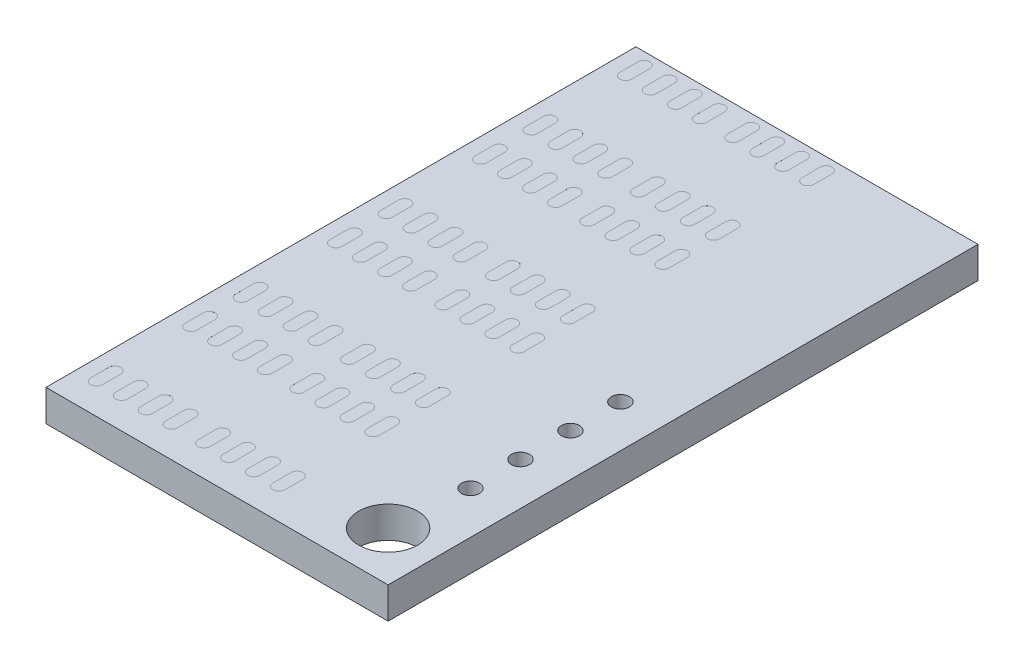
SolidWorks part; units mm, degrees
ref_plane "Front" through (0, 0, 0) normal (0, 0, 1) x (1, 0, 0)
ref_plane "Top" through (0, 0, 0) normal (0, 1, 0) x (1, 0, 0)
ref_plane "Right" through (0, 0, 0) normal (1, 0, 0) x (0, 0, -1)
sketch "Эскиз1" plane through (0, 0, 0) normal (0, 1, 0) x (1, 0, 0)
  line L1 (-8.7, -15) -> (8.7, -15)
  line L2 (-8.7, -15) -> (-8.7, 15)
  line L3 (-8.7, 15) -> (8.7, 15)
  line L4 (8.7, -15) -> (8.7, 15)
  line L5 (-8.7, -15) -> (8.7, 15) construction
  line L6 (-8.7, 15) -> (8.7, -15) construction
  point P0 (0, 0)
  dimension "D1" = 17.4
  dimension "D2" = 30
extrude "Бобышка-Вытянуть1" add sketch "Эскиз1" along normal blind 1.6
sketch "Эскиз2" plane through (0, 1.6, 0) normal (0, 1, 0) x (1, 0, 0)
  line L0 (-8.7, -15) -> (8.7, -15) construction
  line L1 (8.7, -15) -> (8.7, 15) construction
  line L2 (6.541, -8.65) -> (6.541, -1.03) construction
  circle A0 centre (6.2, -12.5) radius 1.5
  circle A1 centre (6.541, -1.03) radius 0.457
  circle A2 centre (6.541, -3.57) radius 0.457
  circle A3 centre (6.541, -6.11) radius 0.457
  circle A4 centre (6.541, -8.65) radius 0.457
  dimension "D1" = 3
  dimension "D4" = 0.914
  dimension "D5" = 0.914
  dimension "D6" = 0.914
  dimension "D7" = 0.914
  dimension "D11" = 2.159
  dimension "D2" = 2.5
  dimension "D3" = 2.5
  dimension "D8" = 2.54
  dimension "D9" = 2.54
  dimension "D10" = 2.54
  dimension "D12" = 13.97
extrude "Вырез-Вытянуть1" cut sketch "Эскиз2" against normal blind 1.6
sketch "Эскиз3" plane through (0, 1.6, 0) normal (0, 1, 0) x (1, 0, 0)
  line L0 (-7.684, 14.39) -> (-7.684, 13.47) construction
  line L1 (-7.384, 14.39) -> (-7.384, 13.47)
  line L2 (-7.984, 14.39) -> (-7.984, 13.47)
  line L3 (8.7, 15) -> (-8.7, 15) construction
  line L4 (-8.7, 15) -> (-8.7, -15) construction
  line L5 (-6.414, 14.39) -> (-6.414, 13.47) construction
  line L6 (-6.114, 14.39) -> (-6.114, 13.47)
  line L7 (-6.714, 14.39) -> (-6.714, 13.47)
  line L8 (-5.144, 14.39) -> (-5.144, 13.47) construction
  line L9 (-4.844, 14.39) -> (-4.844, 13.47)
  line L10 (-5.444, 14.39) -> (-5.444, 13.47)
  line L11 (-3.874, 14.39) -> (-3.874, 13.47) construction
  line L12 (-3.574, 14.39) -> (-3.574, 13.47)
  line L13 (-4.174, 14.39) -> (-4.174, 13.47)
  line L14 (-6.414, 9.59) -> (-6.414, 8.67) construction
  line L15 (-6.114, 9.59) -> (-6.114, 8.67)
  line L16 (-6.714, 9.59) -> (-6.714, 8.67)
  line L17 (-5.144, 9.59) -> (-5.144, 8.67) construction
  line L18 (-4.844, 9.59) -> (-4.844, 8.67)
  line L19 (-5.444, 9.59) -> (-5.444, 8.67)
  line L20 (-3.874, 9.59) -> (-3.874, 8.67) construction
  line L21 (-3.574, 9.59) -> (-3.574, 8.67)
  line L22 (-4.174, 9.59) -> (-4.174, 8.67)
  line L23 (-7.684, 9.59) -> (-7.684, 8.67) construction
  line L24 (-7.384, 9.59) -> (-7.384, 8.67)
  line L25 (-7.984, 9.59) -> (-7.984, 8.67)
  line L26 (-2.224, 14.39) -> (-2.224, 13.47) construction
  line L27 (-1.924, 14.39) -> (-1.924, 13.47)
  line L28 (-2.524, 14.39) -> (-2.524, 13.47)
  line L29 (-0.954, 14.39) -> (-0.954, 13.47) construction
  line L30 (-0.654, 14.39) -> (-0.654, 13.47)
  line L31 (-1.254, 14.39) -> (-1.254, 13.47)
  line L32 (0.316, 14.39) -> (0.316, 13.47) construction
  line L33 (0.616, 14.39) -> (0.616, 13.47)
  line L34 (0.016, 14.39) -> (0.016, 13.47)
  line L35 (1.586, 14.39) -> (1.586, 13.47) construction
  line L36 (1.886, 14.39) -> (1.886, 13.47)
  line L37 (1.286, 14.39) -> (1.286, 13.47)
  line L38 (-0.954, 9.59) -> (-0.954, 8.67) construction
  line L39 (-0.654, 9.59) -> (-0.654, 8.67)
  line L40 (-1.254, 9.59) -> (-1.254, 8.67)
  line L41 (0.316, 9.59) -> (0.316, 8.67) construction
  line L42 (0.616, 9.59) -> (0.616, 8.67)
  line L43 (0.016, 9.59) -> (0.016, 8.67)
  line L44 (1.586, 9.59) -> (1.586, 8.67) construction
  line L45 (1.886, 9.59) -> (1.886, 8.67)
  line L46 (1.286, 9.59) -> (1.286, 8.67)
  line L47 (-2.224, 9.59) -> (-2.224, 8.67) construction
  line L48 (-1.924, 9.59) -> (-1.924, 8.67)
  line L49 (-2.524, 9.59) -> (-2.524, 8.67)
  line L50 (-2.224, 7.02) -> (-2.224, 6.1) construction
  line L51 (-1.924, 7.02) -> (-1.924, 6.1)
  line L52 (-2.524, 7.02) -> (-2.524, 6.1)
  line L53 (-0.954, 7.02) -> (-0.954, 6.1) construction
  line L54 (-0.654, 7.02) -> (-0.654, 6.1)
  line L55 (-1.254, 7.02) -> (-1.254, 6.1)
  line L56 (0.316, 7.02) -> (0.316, 6.1) construction
  line L57 (0.616, 7.02) -> (0.616, 6.1)
  line L58 (0.016, 7.02) -> (0.016, 6.1)
  line L59 (1.586, 7.02) -> (1.586, 6.1) construction
  line L60 (1.886, 7.02) -> (1.886, 6.1)
  line L61 (1.286, 7.02) -> (1.286, 6.1)
  line L62 (-0.954, 2.22) -> (-0.954, 1.3) construction
  line L63 (-0.654, 2.22) -> (-0.654, 1.3)
  line L64 (-1.254, 2.22) -> (-1.254, 1.3)
  line L65 (0.316, 2.22) -> (0.316, 1.3) construction
  line L66 (0.616, 2.22) -> (0.616, 1.3)
  line L67 (0.016, 2.22) -> (0.016, 1.3)
  line L68 (1.586, 2.22) -> (1.586, 1.3) construction
  line L69 (1.886, 2.22) -> (1.886, 1.3)
  line L70 (1.286, 2.22) -> (1.286, 1.3)
  line L71 (-2.224, 2.22) -> (-2.224, 1.3) construction
  line L72 (-1.924, 2.22) -> (-1.924, 1.3)
  line L73 (-2.524, 2.22) -> (-2.524, 1.3)
  line L74 (-2.224, -0.35) -> (-2.224, -1.27) construction
  line L75 (-1.924, -0.35) -> (-1.924, -1.27)
  line L76 (-2.524, -0.35) -> (-2.524, -1.27)
  line L77 (-0.954, -0.35) -> (-0.954, -1.27) construction
  line L78 (-0.654, -0.35) -> (-0.654, -1.27)
  line L79 (-1.254, -0.35) -> (-1.254, -1.27)
  line L80 (0.316, -0.35) -> (0.316, -1.27) construction
  line L81 (0.616, -0.35) -> (0.616, -1.27)
  line L82 (0.016, -0.35) -> (0.016, -1.27)
  line L83 (1.586, -0.35) -> (1.586, -1.27) construction
  line L84 (1.886, -0.35) -> (1.886, -1.27)
  line L85 (1.286, -0.35) -> (1.286, -1.27)
  line L86 (-0.954, -5.15) -> (-0.954, -6.07) construction
  line L87 (-0.654, -5.15) -> (-0.654, -6.07)
  line L88 (-1.254, -5.15) -> (-1.254, -6.07)
  line L89 (0.316, -5.15) -> (0.316, -6.07) construction
  line L90 (0.616, -5.15) -> (0.616, -6.07)
  line L91 (0.016, -5.15) -> (0.016, -6.07)
  line L92 (1.586, -5.15) -> (1.586, -6.07) construction
  line L93 (1.886, -5.15) -> (1.886, -6.07)
  line L94 (1.286, -5.15) -> (1.286, -6.07)
  line L95 (-2.224, -5.15) -> (-2.224, -6.07) construction
  line L96 (-1.924, -5.15) -> (-1.924, -6.07)
  line L97 (-2.524, -5.15) -> (-2.524, -6.07)
  line L98 (-2.224, -7.72) -> (-2.224, -8.64) construction
  line L99 (-1.924, -7.72) -> (-1.924, -8.64)
  line L100 (-2.524, -7.72) -> (-2.524, -8.64)
  line L101 (-0.954, -7.72) -> (-0.954, -8.64) construction
  line L102 (-0.654, -7.72) -> (-0.654, -8.64)
  line L103 (-1.254, -7.72) -> (-1.254, -8.64)
  line L104 (0.316, -7.72) -> (0.316, -8.64) construction
  line L105 (0.616, -7.72) -> (0.616, -8.64)
  line L106 (0.016, -7.72) -> (0.016, -8.64)
  line L107 (1.586, -7.72) -> (1.586, -8.64) construction
  line L108 (1.886, -7.72) -> (1.886, -8.64)
  line L109 (1.286, -7.72) -> (1.286, -8.64)
  line L110 (-0.954, -12.52) -> (-0.954, -13.44) construction
  line L111 (-0.654, -12.52) -> (-0.654, -13.44)
  line L112 (-1.254, -12.52) -> (-1.254, -13.44)
  line L113 (0.316, -12.52) -> (0.316, -13.44) construction
  line L114 (0.616, -12.52) -> (0.616, -13.44)
  line L115 (0.016, -12.52) -> (0.016, -13.44)
  line L116 (1.586, -12.52) -> (1.586, -13.44) construction
  line L117 (1.886, -12.52) -> (1.886, -13.44)
  line L118 (1.286, -12.52) -> (1.286, -13.44)
  line L119 (-2.224, -12.52) -> (-2.224, -13.44) construction
  line L120 (-1.924, -12.52) -> (-1.924, -13.44)
  line L121 (-2.524, -12.52) -> (-2.524, -13.44)
  line L122 (-7.684, 7.02) -> (-7.684, 6.1) construction
  line L123 (-7.384, 7.02) -> (-7.384, 6.1)
  line L124 (-7.984, 7.02) -> (-7.984, 6.1)
  line L125 (-6.414, 7.02) -> (-6.414, 6.1) construction
  line L126 (-6.114, 7.02) -> (-6.114, 6.1)
  line L127 (-6.714, 7.02) -> (-6.714, 6.1)
  line L128 (-5.144, 7.02) -> (-5.144, 6.1) construction
  line L129 (-4.844, 7.02) -> (-4.844, 6.1)
  line L130 (-5.444, 7.02) -> (-5.444, 6.1)
  line L131 (-3.874, 7.02) -> (-3.874, 6.1) construction
  line L132 (-3.574, 7.02) -> (-3.574, 6.1)
  line L133 (-4.174, 7.02) -> (-4.174, 6.1)
  line L134 (-6.414, 2.22) -> (-6.414, 1.3) construction
  line L135 (-6.114, 2.22) -> (-6.114, 1.3)
  line L136 (-6.714, 2.22) -> (-6.714, 1.3)
  line L137 (-5.144, 2.22) -> (-5.144, 1.3) construction
  line L138 (-4.844, 2.22) -> (-4.844, 1.3)
  line L139 (-5.444, 2.22) -> (-5.444, 1.3)
  line L140 (-3.874, 2.22) -> (-3.874, 1.3) construction
  line L141 (-3.574, 2.22) -> (-3.574, 1.3)
  line L142 (-4.174, 2.22) -> (-4.174, 1.3)
  line L143 (-7.684, 2.22) -> (-7.684, 1.3) construction
  line L144 (-7.384, 2.22) -> (-7.384, 1.3)
  line L145 (-7.984, 2.22) -> (-7.984, 1.3)
  line L146 (-7.684, -0.35) -> (-7.684, -1.27) construction
  line L147 (-7.384, -0.35) -> (-7.384, -1.27)
  line L148 (-7.984, -0.35) -> (-7.984, -1.27)
  line L149 (-6.414, -0.35) -> (-6.414, -1.27) construction
  line L150 (-6.114, -0.35) -> (-6.114, -1.27)
  line L151 (-6.714, -0.35) -> (-6.714, -1.27)
  line L152 (-5.144, -0.35) -> (-5.144, -1.27) construction
  line L153 (-4.844, -0.35) -> (-4.844, -1.27)
  line L154 (-5.444, -0.35) -> (-5.444, -1.27)
  line L155 (-3.874, -0.35) -> (-3.874, -1.27) construction
  line L156 (-3.574, -0.35) -> (-3.574, -1.27)
  line L157 (-4.174, -0.35) -> (-4.174, -1.27)
  line L158 (-6.414, -5.15) -> (-6.414, -6.07) construction
  line L159 (-6.114, -5.15) -> (-6.114, -6.07)
  line L160 (-6.714, -5.15) -> (-6.714, -6.07)
  line L161 (-5.144, -5.15) -> (-5.144, -6.07) construction
  line L162 (-4.844, -5.15) -> (-4.844, -6.07)
  line L163 (-5.444, -5.15) -> (-5.444, -6.07)
  line L164 (-3.874, -5.15) -> (-3.874, -6.07) construction
  line L165 (-3.574, -5.15) -> (-3.574, -6.07)
  line L166 (-4.174, -5.15) -> (-4.174, -6.07)
  line L167 (-7.684, -5.15) -> (-7.684, -6.07) construction
  line L168 (-7.384, -5.15) -> (-7.384, -6.07)
  line L169 (-7.984, -5.15) -> (-7.984, -6.07)
  line L170 (-7.684, -7.72) -> (-7.684, -8.64) construction
  line L171 (-7.384, -7.72) -> (-7.384, -8.64)
  line L172 (-7.984, -7.72) -> (-7.984, -8.64)
  line L173 (-6.414, -7.72) -> (-6.414, -8.64) construction
  line L174 (-6.114, -7.72) -> (-6.114, -8.64)
  line L175 (-6.714, -7.72) -> (-6.714, -8.64)
  line L176 (-5.144, -7.72) -> (-5.144, -8.64) construction
  line L177 (-4.844, -7.72) -> (-4.844, -8.64)
  line L178 (-5.444, -7.72) -> (-5.444, -8.64)
  line L179 (-3.874, -7.72) -> (-3.874, -8.64) construction
  line L180 (-3.574, -7.72) -> (-3.574, -8.64)
  line L181 (-4.174, -7.72) -> (-4.174, -8.64)
  line L182 (-6.414, -12.52) -> (-6.414, -13.44) construction
  line L183 (-6.114, -12.52) -> (-6.114, -13.44)
  line L184 (-6.714, -12.52) -> (-6.714, -13.44)
  line L185 (-5.144, -12.52) -> (-5.144, -13.44) construction
  line L186 (-4.844, -12.52) -> (-4.844, -13.44)
  line L187 (-5.444, -12.52) -> (-5.444, -13.44)
  line L188 (-3.874, -12.52) -> (-3.874, -13.44) construction
  line L189 (-3.574, -12.52) -> (-3.574, -13.44)
  line L190 (-4.174, -12.52) -> (-4.174, -13.44)
  line L191 (-7.684, -12.52) -> (-7.684, -13.44) construction
  line L192 (-7.384, -12.52) -> (-7.384, -13.44)
  line L193 (-7.984, -12.52) -> (-7.984, -13.44)
  arc A0 (-7.384, 14.39) -> (-7.984, 14.39) centre (-7.684, 14.39) ccw
  arc A1 (-7.984, 13.47) -> (-7.384, 13.47) centre (-7.684, 13.47) ccw
  arc A2 (-6.114, 14.39) -> (-6.714, 14.39) centre (-6.414, 14.39) ccw
  arc A3 (-6.714, 13.47) -> (-6.114, 13.47) centre (-6.414, 13.47) ccw
  arc A4 (-4.844, 14.39) -> (-5.444, 14.39) centre (-5.144, 14.39) ccw
  arc A5 (-5.444, 13.47) -> (-4.844, 13.47) centre (-5.144, 13.47) ccw
  arc A6 (-3.574, 14.39) -> (-4.174, 14.39) centre (-3.874, 14.39) ccw
  arc A7 (-4.174, 13.47) -> (-3.574, 13.47) centre (-3.874, 13.47) ccw
  arc A8 (-6.114, 9.59) -> (-6.714, 9.59) centre (-6.414, 9.59) ccw
  arc A9 (-6.714, 8.67) -> (-6.114, 8.67) centre (-6.414, 8.67) ccw
  arc A10 (-4.844, 9.59) -> (-5.444, 9.59) centre (-5.144, 9.59) ccw
  arc A11 (-5.444, 8.67) -> (-4.844, 8.67) centre (-5.144, 8.67) ccw
  arc A12 (-3.574, 9.59) -> (-4.174, 9.59) centre (-3.874, 9.59) ccw
  arc A13 (-4.174, 8.67) -> (-3.574, 8.67) centre (-3.874, 8.67) ccw
  arc A14 (-7.384, 9.59) -> (-7.984, 9.59) centre (-7.684, 9.59) ccw
  arc A15 (-7.984, 8.67) -> (-7.384, 8.67) centre (-7.684, 8.67) ccw
  arc A16 (-1.924, 14.39) -> (-2.524, 14.39) centre (-2.224, 14.39) ccw
  arc A17 (-2.524, 13.47) -> (-1.924, 13.47) centre (-2.224, 13.47) ccw
  arc A18 (-0.654, 14.39) -> (-1.254, 14.39) centre (-0.954, 14.39) ccw
  arc A19 (-1.254, 13.47) -> (-0.654, 13.47) centre (-0.954, 13.47) ccw
  arc A20 (0.616, 14.39) -> (0.016, 14.39) centre (0.316, 14.39) ccw
  arc A21 (0.016, 13.47) -> (0.616, 13.47) centre (0.316, 13.47) ccw
  arc A22 (1.886, 14.39) -> (1.286, 14.39) centre (1.586, 14.39) ccw
  arc A23 (1.286, 13.47) -> (1.886, 13.47) centre (1.586, 13.47) ccw
  arc A24 (-0.654, 9.59) -> (-1.254, 9.59) centre (-0.954, 9.59) ccw
  arc A25 (-1.254, 8.67) -> (-0.654, 8.67) centre (-0.954, 8.67) ccw
  arc A26 (0.616, 9.59) -> (0.016, 9.59) centre (0.316, 9.59) ccw
  arc A27 (0.016, 8.67) -> (0.616, 8.67) centre (0.316, 8.67) ccw
  arc A28 (1.886, 9.59) -> (1.286, 9.59) centre (1.586, 9.59) ccw
  arc A29 (1.286, 8.67) -> (1.886, 8.67) centre (1.586, 8.67) ccw
  arc A30 (-1.924, 9.59) -> (-2.524, 9.59) centre (-2.224, 9.59) ccw
  arc A31 (-2.524, 8.67) -> (-1.924, 8.67) centre (-2.224, 8.67) ccw
  arc A32 (-1.924, 7.02) -> (-2.524, 7.02) centre (-2.224, 7.02) ccw
  arc A33 (-2.524, 6.1) -> (-1.924, 6.1) centre (-2.224, 6.1) ccw
  arc A34 (-0.654, 7.02) -> (-1.254, 7.02) centre (-0.954, 7.02) ccw
  arc A35 (-1.254, 6.1) -> (-0.654, 6.1) centre (-0.954, 6.1) ccw
  arc A36 (0.616, 7.02) -> (0.016, 7.02) centre (0.316, 7.02) ccw
  arc A37 (0.016, 6.1) -> (0.616, 6.1) centre (0.316, 6.1) ccw
  arc A38 (1.886, 7.02) -> (1.286, 7.02) centre (1.586, 7.02) ccw
  arc A39 (1.286, 6.1) -> (1.886, 6.1) centre (1.586, 6.1) ccw
  arc A40 (-0.654, 2.22) -> (-1.254, 2.22) centre (-0.954, 2.22) ccw
  arc A41 (-1.254, 1.3) -> (-0.654, 1.3) centre (-0.954, 1.3) ccw
  arc A42 (0.616, 2.22) -> (0.016, 2.22) centre (0.316, 2.22) ccw
  arc A43 (0.016, 1.3) -> (0.616, 1.3) centre (0.316, 1.3) ccw
  arc A44 (1.886, 2.22) -> (1.286, 2.22) centre (1.586, 2.22) ccw
  arc A45 (1.286, 1.3) -> (1.886, 1.3) centre (1.586, 1.3) ccw
  arc A46 (-1.924, 2.22) -> (-2.524, 2.22) centre (-2.224, 2.22) ccw
  arc A47 (-2.524, 1.3) -> (-1.924, 1.3) centre (-2.224, 1.3) ccw
  arc A48 (-1.924, -0.35) -> (-2.524, -0.35) centre (-2.224, -0.35) ccw
  arc A49 (-2.524, -1.27) -> (-1.924, -1.27) centre (-2.224, -1.27) ccw
  arc A50 (-0.654, -0.35) -> (-1.254, -0.35) centre (-0.954, -0.35) ccw
  arc A51 (-1.254, -1.27) -> (-0.654, -1.27) centre (-0.954, -1.27) ccw
  arc A52 (0.616, -0.35) -> (0.016, -0.35) centre (0.316, -0.35) ccw
  arc A53 (0.016, -1.27) -> (0.616, -1.27) centre (0.316, -1.27) ccw
  arc A54 (1.886, -0.35) -> (1.286, -0.35) centre (1.586, -0.35) ccw
  arc A55 (1.286, -1.27) -> (1.886, -1.27) centre (1.586, -1.27) ccw
  arc A56 (-0.654, -5.15) -> (-1.254, -5.15) centre (-0.954, -5.15) ccw
  arc A57 (-1.254, -6.07) -> (-0.654, -6.07) centre (-0.954, -6.07) ccw
  arc A58 (0.616, -5.15) -> (0.016, -5.15) centre (0.316, -5.15) ccw
  arc A59 (0.016, -6.07) -> (0.616, -6.07) centre (0.316, -6.07) ccw
  arc A60 (1.886, -5.15) -> (1.286, -5.15) centre (1.586, -5.15) ccw
  arc A61 (1.286, -6.07) -> (1.886, -6.07) centre (1.586, -6.07) ccw
  arc A62 (-1.924, -5.15) -> (-2.524, -5.15) centre (-2.224, -5.15) ccw
  arc A63 (-2.524, -6.07) -> (-1.924, -6.07) centre (-2.224, -6.07) ccw
  arc A64 (-1.924, -7.72) -> (-2.524, -7.72) centre (-2.224, -7.72) ccw
  arc A65 (-2.524, -8.64) -> (-1.924, -8.64) centre (-2.224, -8.64) ccw
  arc A66 (-0.654, -7.72) -> (-1.254, -7.72) centre (-0.954, -7.72) ccw
  arc A67 (-1.254, -8.64) -> (-0.654, -8.64) centre (-0.954, -8.64) ccw
  arc A68 (0.616, -7.72) -> (0.016, -7.72) centre (0.316, -7.72) ccw
  arc A69 (0.016, -8.64) -> (0.616, -8.64) centre (0.316, -8.64) ccw
  arc A70 (1.886, -7.72) -> (1.286, -7.72) centre (1.586, -7.72) ccw
  arc A71 (1.286, -8.64) -> (1.886, -8.64) centre (1.586, -8.64) ccw
  arc A72 (-0.654, -12.52) -> (-1.254, -12.52) centre (-0.954, -12.52) ccw
  arc A73 (-1.254, -13.44) -> (-0.654, -13.44) centre (-0.954, -13.44) ccw
  arc A74 (0.616, -12.52) -> (0.016, -12.52) centre (0.316, -12.52) ccw
  arc A75 (0.016, -13.44) -> (0.616, -13.44) centre (0.316, -13.44) ccw
  arc A76 (1.886, -12.52) -> (1.286, -12.52) centre (1.586, -12.52) ccw
  arc A77 (1.286, -13.44) -> (1.886, -13.44) centre (1.586, -13.44) ccw
  arc A78 (-1.924, -12.52) -> (-2.524, -12.52) centre (-2.224, -12.52) ccw
  arc A79 (-2.524, -13.44) -> (-1.924, -13.44) centre (-2.224, -13.44) ccw
  arc A80 (-7.384, 7.02) -> (-7.984, 7.02) centre (-7.684, 7.02) ccw
  arc A81 (-7.984, 6.1) -> (-7.384, 6.1) centre (-7.684, 6.1) ccw
  arc A82 (-6.114, 7.02) -> (-6.714, 7.02) centre (-6.414, 7.02) ccw
  arc A83 (-6.714, 6.1) -> (-6.114, 6.1) centre (-6.414, 6.1) ccw
  arc A84 (-4.844, 7.02) -> (-5.444, 7.02) centre (-5.144, 7.02) ccw
  arc A85 (-5.444, 6.1) -> (-4.844, 6.1) centre (-5.144, 6.1) ccw
  arc A86 (-3.574, 7.02) -> (-4.174, 7.02) centre (-3.874, 7.02) ccw
  arc A87 (-4.174, 6.1) -> (-3.574, 6.1) centre (-3.874, 6.1) ccw
  arc A88 (-6.114, 2.22) -> (-6.714, 2.22) centre (-6.414, 2.22) ccw
  arc A89 (-6.714, 1.3) -> (-6.114, 1.3) centre (-6.414, 1.3) ccw
  arc A90 (-4.844, 2.22) -> (-5.444, 2.22) centre (-5.144, 2.22) ccw
  arc A91 (-5.444, 1.3) -> (-4.844, 1.3) centre (-5.144, 1.3) ccw
  arc A92 (-3.574, 2.22) -> (-4.174, 2.22) centre (-3.874, 2.22) ccw
  arc A93 (-4.174, 1.3) -> (-3.574, 1.3) centre (-3.874, 1.3) ccw
  arc A94 (-7.384, 2.22) -> (-7.984, 2.22) centre (-7.684, 2.22) ccw
  arc A95 (-7.984, 1.3) -> (-7.384, 1.3) centre (-7.684, 1.3) ccw
  arc A96 (-7.384, -0.35) -> (-7.984, -0.35) centre (-7.684, -0.35) ccw
  arc A97 (-7.984, -1.27) -> (-7.384, -1.27) centre (-7.684, -1.27) ccw
  arc A98 (-6.114, -0.35) -> (-6.714, -0.35) centre (-6.414, -0.35) ccw
  arc A99 (-6.714, -1.27) -> (-6.114, -1.27) centre (-6.414, -1.27) ccw
  arc A100 (-4.844, -0.35) -> (-5.444, -0.35) centre (-5.144, -0.35) ccw
  arc A101 (-5.444, -1.27) -> (-4.844, -1.27) centre (-5.144, -1.27) ccw
  arc A102 (-3.574, -0.35) -> (-4.174, -0.35) centre (-3.874, -0.35) ccw
  arc A103 (-4.174, -1.27) -> (-3.574, -1.27) centre (-3.874, -1.27) ccw
  arc A104 (-6.114, -5.15) -> (-6.714, -5.15) centre (-6.414, -5.15) ccw
  arc A105 (-6.714, -6.07) -> (-6.114, -6.07) centre (-6.414, -6.07) ccw
  arc A106 (-4.844, -5.15) -> (-5.444, -5.15) centre (-5.144, -5.15) ccw
  arc A107 (-5.444, -6.07) -> (-4.844, -6.07) centre (-5.144, -6.07) ccw
  arc A108 (-3.574, -5.15) -> (-4.174, -5.15) centre (-3.874, -5.15) ccw
  arc A109 (-4.174, -6.07) -> (-3.574, -6.07) centre (-3.874, -6.07) ccw
  arc A110 (-7.384, -5.15) -> (-7.984, -5.15) centre (-7.684, -5.15) ccw
  arc A111 (-7.984, -6.07) -> (-7.384, -6.07) centre (-7.684, -6.07) ccw
  arc A112 (-7.384, -7.72) -> (-7.984, -7.72) centre (-7.684, -7.72) ccw
  arc A113 (-7.984, -8.64) -> (-7.384, -8.64) centre (-7.684, -8.64) ccw
  arc A114 (-6.114, -7.72) -> (-6.714, -7.72) centre (-6.414, -7.72) ccw
  arc A115 (-6.714, -8.64) -> (-6.114, -8.64) centre (-6.414, -8.64) ccw
  arc A116 (-4.844, -7.72) -> (-5.444, -7.72) centre (-5.144, -7.72) ccw
  arc A117 (-5.444, -8.64) -> (-4.844, -8.64) centre (-5.144, -8.64) ccw
  arc A118 (-3.574, -7.72) -> (-4.174, -7.72) centre (-3.874, -7.72) ccw
  arc A119 (-4.174, -8.64) -> (-3.574, -8.64) centre (-3.874, -8.64) ccw
  arc A120 (-6.114, -12.52) -> (-6.714, -12.52) centre (-6.414, -12.52) ccw
  arc A121 (-6.714, -13.44) -> (-6.114, -13.44) centre (-6.414, -13.44) ccw
  arc A122 (-4.844, -12.52) -> (-5.444, -12.52) centre (-5.144, -12.52) ccw
  arc A123 (-5.444, -13.44) -> (-4.844, -13.44) centre (-5.144, -13.44) ccw
  arc A124 (-3.574, -12.52) -> (-4.174, -12.52) centre (-3.874, -12.52) ccw
  arc A125 (-4.174, -13.44) -> (-3.574, -13.44) centre (-3.874, -13.44) ccw
  arc A126 (-7.384, -12.52) -> (-7.984, -12.52) centre (-7.684, -12.52) ccw
  arc A127 (-7.984, -13.44) -> (-7.384, -13.44) centre (-7.684, -13.44) ccw
  point P2 (-7.684, 13.93)
  point P16 (-6.414, 13.93)
  point P23 (-5.144, 13.93)
  point P30 (-3.874, 13.93)
  point P37 (-6.414, 9.13)
  point P44 (-5.144, 9.13)
  point P51 (-3.874, 9.13)
  point P58 (-7.684, 9.13)
  point P65 (-2.224, 13.93)
  point P72 (-0.954, 13.93)
  point P79 (0.316, 13.93)
  point P86 (1.586, 13.93)
  point P93 (-0.954, 9.13)
  point P100 (0.316, 9.13)
  point P107 (1.586, 9.13)
  point P114 (-2.224, 9.13)
  point P121 (-2.224, 6.56)
  point P128 (-0.954, 6.56)
  point P135 (0.316, 6.56)
  point P142 (1.586, 6.56)
  point P149 (-0.954, 1.76)
  point P156 (0.316, 1.76)
  point P163 (1.586, 1.76)
  point P170 (-2.224, 1.76)
  point P177 (-2.224, -0.81)
  point P184 (-0.954, -0.81)
  point P191 (0.316, -0.81)
  point P198 (1.586, -0.81)
  point P205 (-0.954, -5.61)
  point P212 (0.316, -5.61)
  point P219 (1.586, -5.61)
  point P226 (-2.224, -5.61)
  point P233 (-2.224, -8.18)
  point P240 (-0.954, -8.18)
  point P247 (0.316, -8.18)
  point P254 (1.586, -8.18)
  point P261 (-0.954, -12.98)
  point P268 (0.316, -12.98)
  point P275 (1.586, -12.98)
  point P282 (-2.224, -12.98)
  point P289 (-7.684, 6.56)
  point P296 (-6.414, 6.56)
  point P303 (-5.144, 6.56)
  point P310 (-3.874, 6.56)
  point P317 (-6.414, 1.76)
  point P324 (-5.144, 1.76)
  point P331 (-3.874, 1.76)
  point P338 (-7.684, 1.76)
  point P345 (-7.684, -0.81)
  point P352 (-6.414, -0.81)
  point P359 (-5.144, -0.81)
  point P366 (-3.874, -0.81)
  point P373 (-6.414, -5.61)
  point P380 (-5.144, -5.61)
  point P387 (-3.874, -5.61)
  point P394 (-7.684, -5.61)
  point P401 (-7.684, -8.18)
  point P408 (-6.414, -8.18)
  point P415 (-5.144, -8.18)
  point P422 (-3.874, -8.18)
  point P429 (-6.414, -12.98)
  point P436 (-5.144, -12.98)
  point P443 (-3.874, -12.98)
  point P450 (-7.684, -12.98)
  dimension "D1" = 0.92
  dimension "D2" = 0.6
  dimension "D3" = 1.07
  dimension "D4" = 1.016
  dimension "D5" = 4
  dimension "D6" = 2
  dimension "D7" = 2
  dimension "D8" = 4
extrude "Вырез-Вытянуть2" cut sketch "Эскиз3" against normal blind 0.0001
